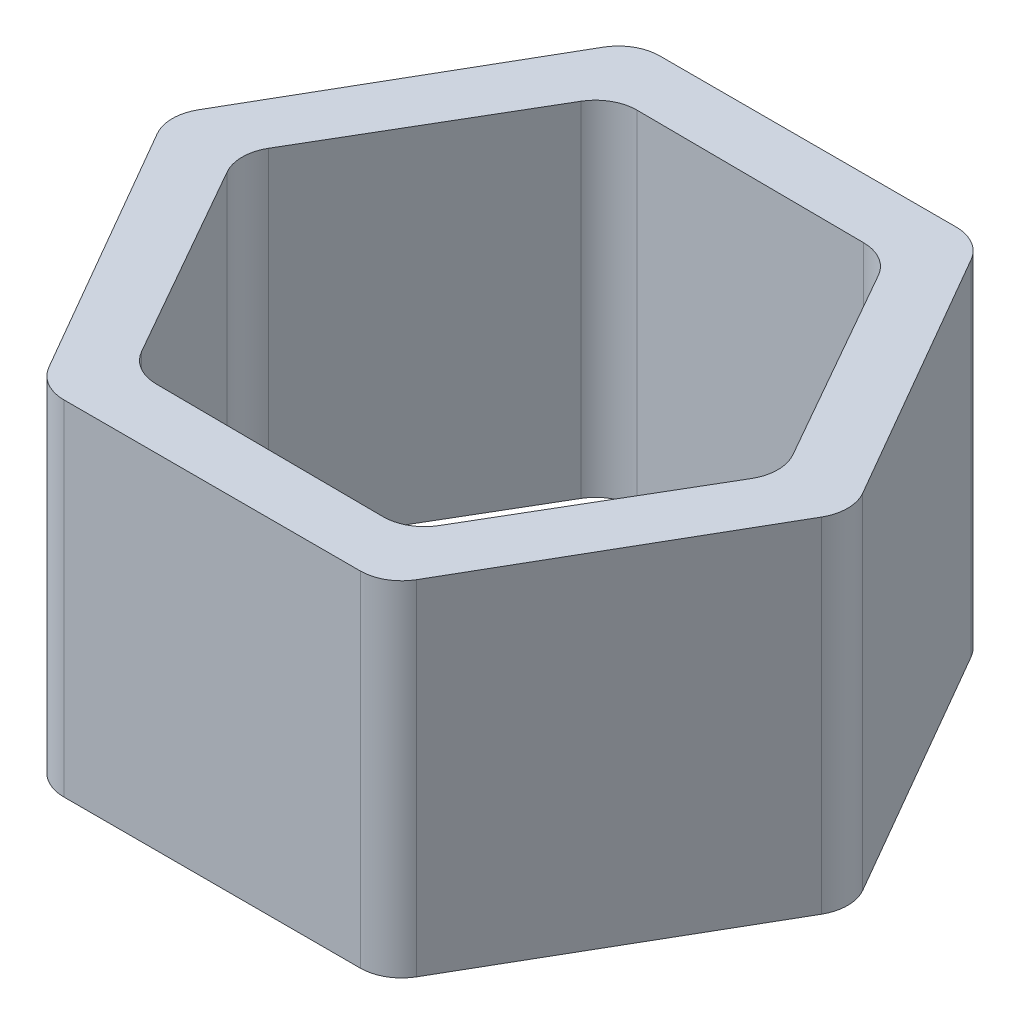
SolidWorks part; units mm, degrees
ref_plane "Alzado" through (0, 0, 0) normal (0, 0, 1) x (1, 0, 0)
ref_plane "Planta" through (0, 0, 0) normal (0, 1, 0) x (1, 0, 0)
ref_plane "Vista lateral" through (0, 0, 0) normal (1, 0, 0) x (0, 0, -1)
sketch "Croquis1" plane through (0, 0, 0) normal (0, 1, 0) x (1, 0, 0)
  line L1 (-50, -86.6025) -> (50, -86.6025)
  line L2 (50, -86.6025) -> (100, 0)
  line L3 (100, 0) -> (50, 86.6025)
  line L4 (50, 86.6025) -> (-50, 86.6025)
  line L5 (-50, 86.6025) -> (-100, 0)
  line L6 (-100, 0) -> (-50, -86.6025)
  circle A0 centre (0, 0) radius 86.6025 construction
  dimension "D1" = 100
extrude "Saliente-Extruir2" add sketch "Croquis1" along normal blind 100
sketch "Croquis3" plane through (0, 100, 0) normal (0, 1, 0) x (1, 0, 0)
  line L1 (39.6136, -69.6861) -> (80.1567, -0.5367)
  line L2 (80.1567, -0.5367) -> (40.5431, 69.1494)
  line L3 (40.5431, 69.1494) -> (-39.6136, 69.6861)
  line L4 (-39.6136, 69.6861) -> (-80.1567, 0.5367)
  line L5 (-80.1567, 0.5367) -> (-40.5431, -69.1494)
  line L6 (-40.5431, -69.1494) -> (39.6136, -69.6861)
  circle A0 centre (0, 0) radius 69.4193 construction
extrude "Cortar-Extruir1" cut sketch "Croquis3" against normal blind 100
fillet "Redondeo1" radius 12 6 edges at (-100, 50, 0) (-50, 50, 86.6025) (50, 50, 86.6025) (50, 50, -86.6025) (100, 50, 0) (-50, 50, -86.6025)
fillet "Redondeo2" radius 12 6 edges at (-40.5431, 50, 69.1494) (39.6136, 50, 69.6861) (80.1567, 50, 0.5367) (40.5431, 50, -69.1494) (-39.6136, 50, -69.6861) (-80.1567, 50, -0.5367)
